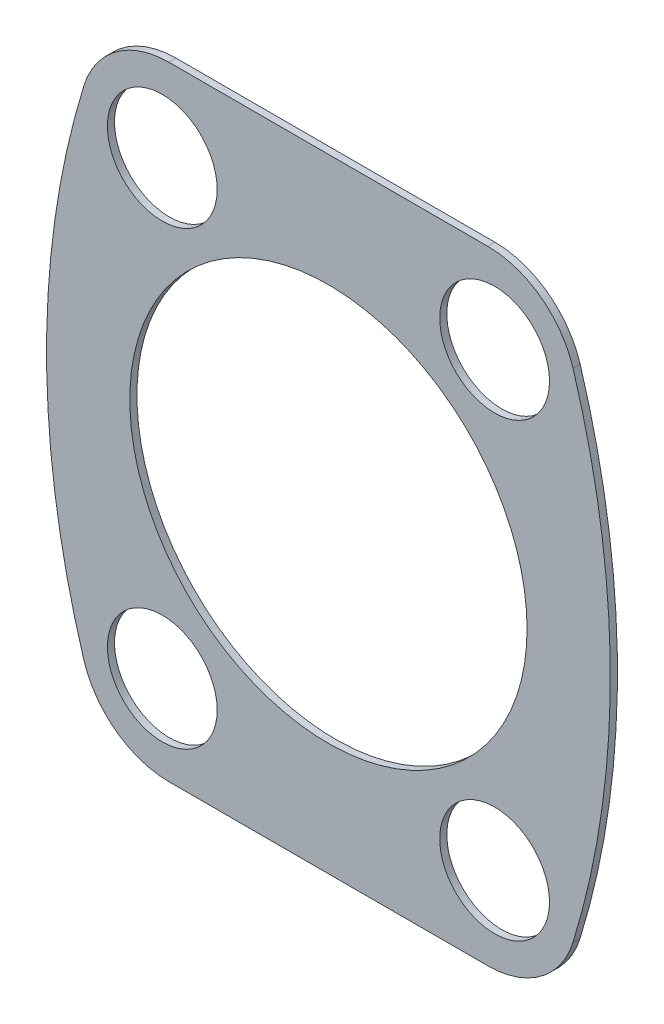
SolidWorks part; units mm, degrees
material "TESNIT BA-R"
ref_plane "Front Plane" through (0, 0, 0) normal (0, 0, 1) x (1, 0, 0)
ref_plane "Top Plane" through (0, 0, 0) normal (0, 1, 0) x (1, 0, 0)
ref_plane "Right Plane" through (0, 0, 0) normal (1, 0, 0) x (0, 0, -1)
sketch "Sketch1" plane through (0, 0, 0) normal (0, 0, 1) x (1, 0, 0)
  line L2 (-26.875, -52.5) -> (26.875, -52.5)
  line L3 (26.875, 52.5) -> (-26.875, 52.5)
  line L4 (-26.875, -52.5) -> (26.875, -52.5)
  line L5 (26.875, 52.5) -> (-26.875, 52.5)
  circle A0 centre (-28, -38) radius 9.25 construction
  circle A1 centre (28, -38) radius 9.25 construction
  circle A2 centre (28, 38) radius 9.25 construction
  circle A3 centre (-28, 38) radius 9.25 construction
  circle A4 centre (-28, -38) radius 9.25
  circle A5 centre (28, -38) radius 9.25
  arc A6 (-26.875, 52.5) -> (-41.2149, 41.901) centre (-26.875, 37.5) ccw
  arc A7 (-41.2149, 41.901) -> (-41.2149, -41.901) centre (95.3125, 0) ccw
  arc A8 (-41.2149, -41.901) -> (-26.875, -52.5) centre (-26.875, -37.5) ccw
  arc A9 (26.875, -52.5) -> (41.2149, -41.901) centre (26.875, -37.5) ccw
  arc A10 (41.2149, -41.901) -> (41.2149, 41.901) centre (-95.3125, 0) ccw
  arc A11 (41.2149, 41.901) -> (26.875, 52.5) centre (26.875, 37.5) ccw
  arc A12 (-26.875, 52.5) -> (-41.2149, 41.901) centre (-26.875, 37.5) ccw
  arc A13 (-41.2149, 41.901) -> (-41.2149, -41.901) centre (95.3125, 0) ccw
  arc A14 (-41.2149, -41.901) -> (-26.875, -52.5) centre (-26.875, -37.5) ccw
  arc A15 (26.875, -52.5) -> (41.2149, -41.901) centre (26.875, -37.5) ccw
  arc A16 (41.2149, -41.901) -> (41.2149, 41.901) centre (-95.3125, 0) ccw
  arc A17 (41.2149, 41.901) -> (26.875, 52.5) centre (26.875, 37.5) ccw
  circle A18 centre (28, 38) radius 9.25
  circle A19 centre (-28, 38) radius 9.25
  circle A22 centre (0, 0) radius 33.475
  circle A23 centre (0, 0) radius 33.475
  dimension "D1" = 0
  dimension "D2" = 1
extrude "Extrude2" add sketch "Sketch1" along normal blind 1.2
